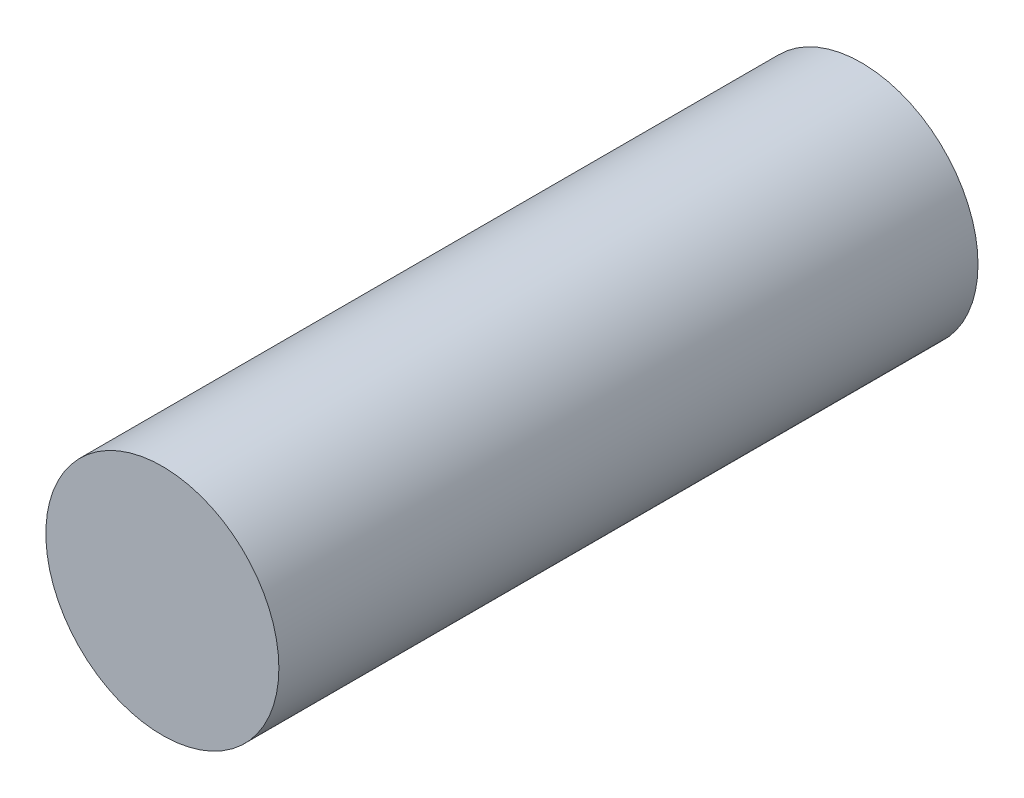
SolidWorks part; units mm, degrees
material "Pine"
ref_plane "Front Plane" through (0, 0, 0) normal (0, 0, 1) x (1, 0, 0)
ref_plane "Top Plane" through (0, 0, 0) normal (0, 1, 0) x (1, 0, 0)
ref_plane "Right Plane" through (0, 0, 0) normal (1, 0, 0) x (0, 0, -1)
sketch "Sketch1" plane through (0, 0, 0) normal (0, 0, 1) x (1, 0, 0)
  circle A0 centre (0, 0) radius 7.9375
  dimension "D1" = 15.875
extrude "Boss-Extrude1" add sketch "Sketch1" along normal blind 47.625
sketch "Sketch2" [suppressed] plane through (0, 0, 47.625) normal (0, 0, 1) x (1, 0, 0)
  circle A1 centre (0, 0) radius 7.9375
  circle A2 centre (0, 0) radius 7.9375
  dimension "D1" = 0
extrude "Cut-Extrude1" [suppressed] cut sketch "Sketch2" against normal offset from surface (9.525 mm away) 38.1
